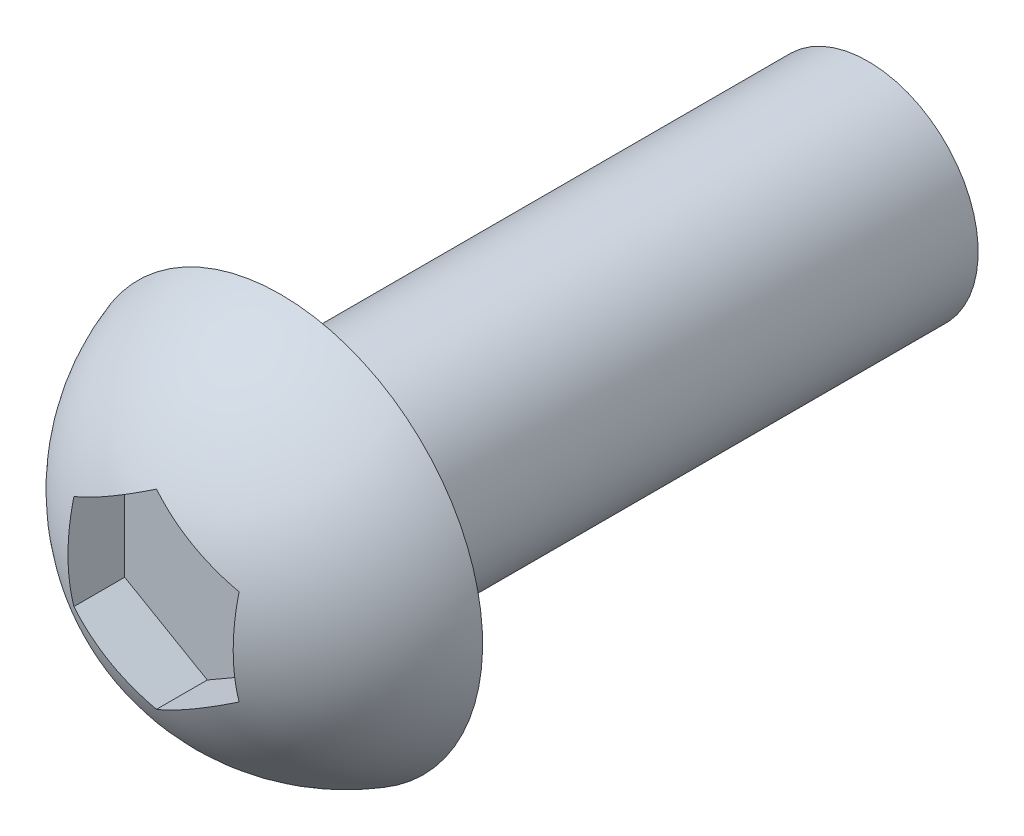
SolidWorks part; units mm, degrees
ref_plane "Front Plane" through (0, 0, 0) normal (1, 0, 0) x (0, 1, 0)
ref_plane "Top Plane" through (0, 0, 0) normal (0, 0, 1) x (0, 1, 0)
ref_plane "Right Plane" through (0, 0, 0) normal (0, 1, 0) x (-1, 0, 0)
sketch "Sketch1" plane through (0, 0, 0) normal (1, 0, 0) x (0, 1, 0)
  line L1 (0, -5) -> (1.5, -5)
  line L2 (0, -5) -> (0, 3)
  line L4 (1.5, -5) -> (1.5, 3)
  line L5 (0, -5) -> (1.5, 3) construction
  line L6 (0, 3) -> (1.5, -5) construction
  line L9 (0, 3) -> (0, 5)
  line L10 (1.5, 3) -> (2.75, 3)
  line L11 (-2.75, 5) -> (2.75, -5) construction
  line L12 (0, -5) -> (-1.5, -5) construction
  line L13 (0, -5) -> (0, 3) construction
  line L14 (0, 3) -> (-1.5, 3) construction
  line L15 (-1.5, -5) -> (-1.5, 3) construction
  line L16 (0, -5) -> (-1.5, 3) construction
  line L17 (0, 3) -> (-1.5, -5) construction
  line L18 (0, 3) -> (-2.75, 3) construction
  line L19 (0, 3) -> (0, 5) construction
  line L20 (0, 5) -> (-2.75, 5) construction
  line L21 (-2.75, 3) -> (-2.75, 5) construction
  line L22 (0, 3) -> (-2.75, 5) construction
  line L23 (0, 5) -> (-2.75, 3) construction
  arc A3 (2.75, 3) -> (0, 5) centre (0, 2.1094) ccw
  circle A4 centre (0, 2.1094) radius 2.8906 construction
  point P4 (0.75, -1)
  point P12 (-0.75, -1)
  point P16 (-1.375, 4)
  point P17 (0, 0)
  point P19 (0, 0)
  point P21 (0, 0)
  point P22 (0, 0)
  point P23 (0, 0.9633)
  dimension "D1" = 8
  dimension "D2" = 2.75
  dimension "D5" = 2.75
  dimension "D3" = 1.5
  dimension "D4" = 5
  dimension "D6" = 2
revolve "Revolve1" add sketch "Sketch1" angle 360 about L9
sketch "Sketch2" plane through (0, 0, 0) normal (0, 0, 1) x (0, 1, 0)
  line L1 (1.299, 0) -> (0.6495, 1.125)
  line L2 (0.6495, 1.125) -> (-0.6495, 1.125)
  line L3 (-0.6495, 1.125) -> (-1.299, 0)
  line L4 (-1.299, 0) -> (-0.6495, -1.125)
  line L5 (-0.6495, -1.125) -> (0.6495, -1.125)
  line L6 (0.6495, -1.125) -> (1.299, 0)
  circle A0 centre (0, 0) radius 1.125 construction
  dimension "D1" = 2.25
extrude "Cut-Extrude1" cut sketch "Sketch2" against normal blind 1 from offset 5
